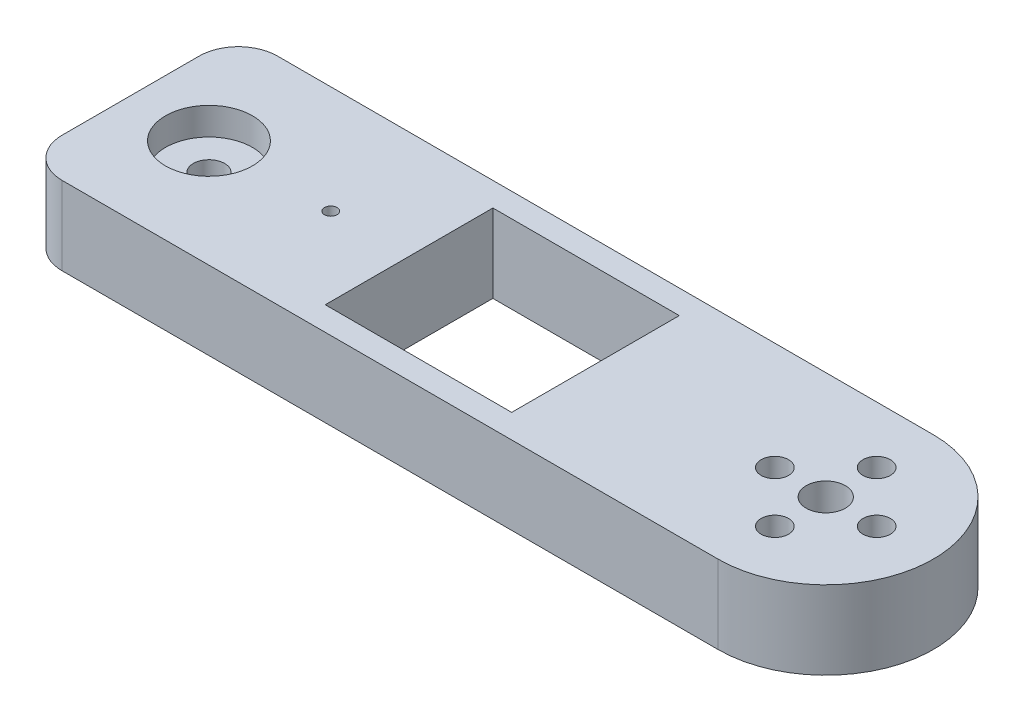
SolidWorks part; units mm, degrees
material "ABS"
ref_plane "Front Plane" through (0, 0, 0) normal (0, 0, 1) x (1, 0, 0)
ref_plane "Top Plane" through (0, 0, 0) normal (0, 1, 0) x (1, 0, 0)
ref_plane "Right Plane" through (0, 0, 0) normal (1, 0, 0) x (0, 0, -1)
sketch "Sketch1" plane through (0, 0, 0) normal (0, 1, 0) x (1, 0, 0)
  line L1 (75, -27.5) -> (-75, -27.5)
  line L2 (75, -27.5) -> (75, 27.5)
  line L3 (75, 27.5) -> (-75, 27.5)
  line L4 (-75, -27.5) -> (-75, 27.5)
  line L5 (75, -27.5) -> (-75, 27.5) construction
  line L6 (75, 27.5) -> (-75, -27.5) construction
  point P0 (0, 0)
  dimension "D1" = 150
  dimension "D2" = 55
extrude "Boss-Extrude1" add sketch "Sketch1" along normal blind 20
sketch "Sketch2" plane through (0, 0, 0) normal (0, -1, 0) x (1, 0, 0)
  line L0 (-75, 27.5) -> (-75, -27.5)
  line L1 (75, 27.5) -> (75, -27.5)
  line L2 (75, -27.5) -> (-75, -27.5) construction
  line L3 (0, 27.5) -> (0, 0) construction
  line L4 (-75, 27.5) -> (75, 27.5) construction
  line L5 (-75, 27.5) -> (-102.5, 27.5)
  line L6 (-102.5, 27.5) -> (-102.5, -27.5)
  line L7 (-102.5, -27.5) -> (-75, -27.5)
  line L8 (75, 27.5) -> (75, -27.5) construction
  line L9 (-75, -27.5) -> (-75, 27.5) construction
  arc A0 (-75, -27.5) -> (-75, 27.5) centre (-75, 0) cw construction
  arc A1 (75, -27.5) -> (75, 27.5) centre (75, 0) ccw
extrude "Boss-Extrude2" add sketch "Sketch2" against normal up to surface (20 mm away) up to face at (0, 20, 0)
sketch "Sketch4" plane through (0, 20, 0) normal (0, 1, 0) x (1, 0, 0)
  circle A0 centre (75, 0) radius 12.065
  dimension "D1" = 24.13
hole_wizard "M8 Clearance Hole1" positions "Sketch5" profile "Sketch6" hole size "M8" standard "ANSI Metric" end condition through all
sketch "Sketch5" plane through (0, 0, 0) normal (0, -1, 0) x (-1, 0, 0)
  point P0 (-75, 0)
sketch "Sketch6" plane through (75, 0, 0) normal (1, 0, 0) x (0, 0, -1)
  line L0 (0, 0) -> (0, 20)
  line L1 (0, 20) -> (5, 20)
  line L2 (5, 20) -> (5, 0)
  line L5 (5, 0) -> (0, 0)
  line L11 (0, -6.35) -> (0, 107.95) construction
  dimension "Thru Hole Dia." = 10
  dimension "Thru Hole Depth" = 20
hole_wizard "M6 Clearance Hole1" positions "Sketch9" profile "Sketch8" hole size "M6" standard "ANSI Metric" end condition through all
sketch "Sketch9" plane through (0, 20, 0) normal (0, 1, 0) x (1, 0, 0)
  circle A2 centre (75, 0) radius 13
  point P8 (75, 13)
  point P12 (62, 0)
  point P14 (88, 0)
  point P16 (75, -13)
  dimension "D2" = 26
sketch "Sketch8" plane through (75, 20, -13) normal (1, 0, 0) x (0, 0, 1)
  line L0 (0, 0) -> (0, 20)
  line L1 (0, 20) -> (3.5, 20)
  line L2 (3.5, 20) -> (3.5, 0)
  line L5 (3.5, 0) -> (0, 0)
  line L11 (0, -6.35) -> (0, 107.95) construction
  dimension "Thru Hole Dia." = 7
  dimension "Thru Hole Depth" = 20
fillet "Fillet1" radius 10 2 edges at (-102.5, 10, 27.5) (-102.5, 10, -27.5)
sketch "Sketch11" plane through (0, 0, 0) normal (0, -1, 0) x (1, 0, 0)
  line L1 (-31.2, -21.2) -> (11.2, -21.2)
  line L2 (-31.2, -21.2) -> (-31.2, 21.2)
  line L3 (-31.2, 21.2) -> (11.2, 21.2)
  line L4 (11.2, -21.2) -> (11.2, 21.2)
  line L5 (-31.2, -21.2) -> (11.2, 21.2) construction
  line L6 (-31.2, 21.2) -> (11.2, -21.2) construction
  point P4 (-10, 0)
  dimension "D1" = 42.4
  dimension "D2" = 85
extrude "Cut-Extrude1" cut sketch "Sketch11" against normal through all
sketch "Sketch12" plane through (0, 20, 0) normal (0, 1, 0) x (1, 0, 0)
  line L0 (-102.5, -17.5) -> (-102.5, 17.5) construction
  circle A0 centre (-82.5, 0) radius 4
  dimension "D1" = 8
  dimension "D2" = 20
extrude "Cut-Extrude2" cut sketch "Sketch12" against normal through all
sketch "Sketch13" plane through (0, 0, 0) normal (0, -1, 0) x (1, 0, 0)
  line L0 (11.2, 21.2) -> (-31.2, 21.2) construction
  line L1 (-31.4, -21.4) -> (16.2, -21.4)
  line L2 (-31.4, -21.4) -> (-31.4, 21.4)
  line L3 (-31.4, 21.4) -> (16.2, 21.4)
  line L4 (16.2, -21.4) -> (16.2, 21.4)
  line L5 (-31.4, -21.4) -> (16.2, 21.4) construction
  line L6 (-31.4, 21.4) -> (16.2, -21.4) construction
  line L7 (11.2, -21.2) -> (11.2, 21.2) construction
  line L8 (-31.2, 21.2) -> (-31.2, -21.2) construction
  line L9 (-31.2, -21.2) -> (11.2, -21.2) construction
  point P4 (-7.6, 0)
  dimension "D1" = 0.2
  dimension "D2" = 5
  dimension "D3" = 0.2
  dimension "D4" = 0.2
extrude "Cut-Extrude3" cut sketch "Sketch13" against normal through all
sketch "Sketch14" plane through (0, 0, 0) normal (0, -1, 0) x (1, 0, 0)
  line L0 (93.9691, 3.4463) -> (88, 6.8925)
  line L1 (71.5537, 18.9691) -> (68.1075, 13)
  line L2 (68.1075, 13) -> (71.5537, 7.0309)
  line L3 (71.5537, 7.0309) -> (78.4463, 7.0309)
  line L4 (78.4463, 7.0309) -> (81.8925, 13)
  line L5 (81.8925, 13) -> (78.4463, 18.9691)
  line L6 (78.4463, 18.9691) -> (71.5537, 18.9691)
  line L7 (88, 6.8925) -> (82.0309, 3.4463)
  line L8 (82.0309, 3.4463) -> (82.0309, -3.4463)
  line L9 (82.0309, -3.4463) -> (88, -6.8925)
  line L10 (88, -6.8925) -> (93.9691, -3.4463)
  line L11 (93.9691, -3.4463) -> (93.9691, 3.4463)
  line L12 (78.4463, -18.9691) -> (81.8925, -13)
  line L13 (81.8925, -13) -> (78.4463, -7.0309)
  line L14 (78.4463, -7.0309) -> (71.5537, -7.0309)
  line L15 (71.5537, -7.0309) -> (68.1075, -13)
  line L16 (68.1075, -13) -> (71.5537, -18.9691)
  line L17 (71.5537, -18.9691) -> (78.4463, -18.9691)
  line L18 (56.0309, -3.4463) -> (62, -6.8925)
  line L19 (62, -6.8925) -> (67.9691, -3.4463)
  line L20 (67.9691, -3.4463) -> (67.9691, 3.4463)
  line L21 (67.9691, 3.4463) -> (62, 6.8925)
  line L22 (62, 6.8925) -> (56.0309, 3.4463)
  line L23 (56.0309, 3.4463) -> (56.0309, -3.4463)
  circle A0 centre (75, 13) radius 5.9691 construction
  circle A1 centre (75, 0) radius 12.065 construction
  point P30 (75, 0)
  dimension "D1" = 6.8925
  dimension "D2" = 4
extrude "Cut-Extrude4" cut sketch "Sketch14" against normal blind 6.5
sketch "Sketch15" plane through (0, 20, 0) normal (0, 1, 0) x (1, 0, 0)
  circle A0 centre (-82.5, 0) radius 11.1
  dimension "D1" = 22.2
extrude "Cut-Extrude5" cut sketch "Sketch15" against normal blind 7
hole_wizard "Ø3.0mm Dowel Hole1" positions "Sketch17" profile "Sketch18" hole size "Ø3.0" standard "ANSI Metric" end condition through all
sketch "Sketch17" plane through (0, 0, 0) normal (0, -1, 0) x (-1, 0, 0)
  line L0 (31.4, -21.4) -> (31.4, 21.4) construction
  point P0 (51.4, 0)
  point P5 (0, 0)
  dimension "D1" = 20
sketch "Sketch18" plane through (-51.4, 0, 0) normal (1, 0, 0) x (0, 0, -1)
  line L0 (0, 0) -> (0, 20)
  line L1 (0, 20) -> (1.6, 20)
  line L2 (1.6, 20) -> (1.6, 0)
  line L5 (1.6, 0) -> (0, 0)
  line L11 (0, -6.35) -> (0, 107.95) construction
  dimension "Thru Hole Dia." = 3.2
  dimension "Thru Hole Depth" = 20
